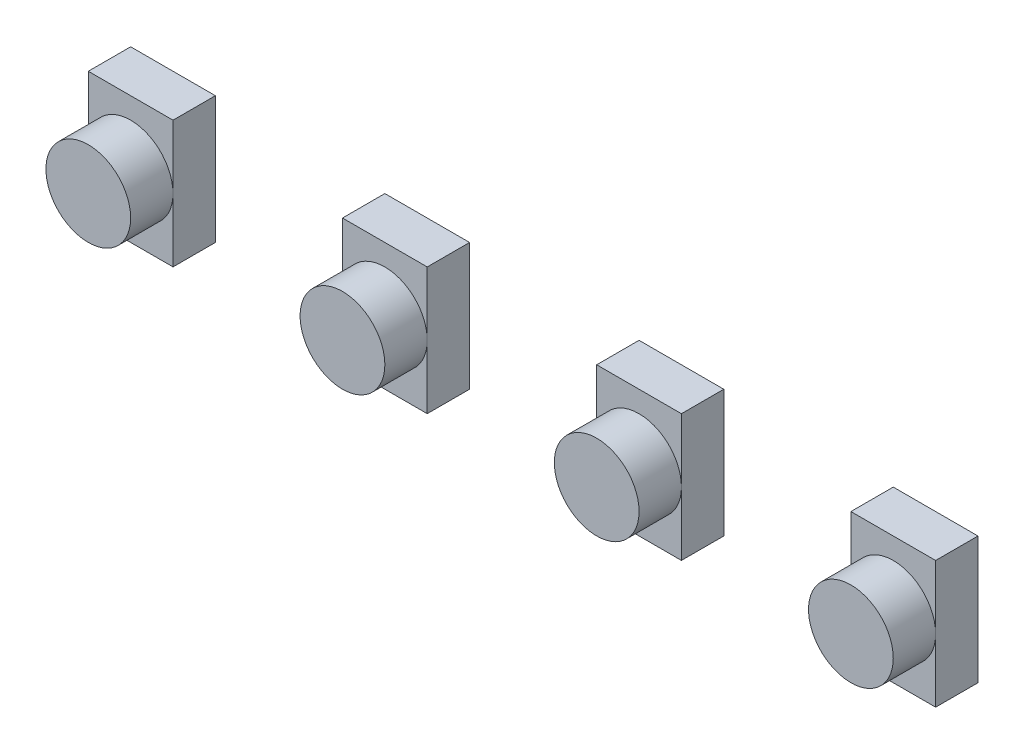
SolidWorks part; units mm, degrees
ref_plane "前视基准面" through (0, 0, 0) normal (0, 0, 1) x (1, 0, 0)
ref_plane "上视基准面" through (0, 0, 0) normal (0, 1, 0) x (1, 0, 0)
ref_plane "右视基准面" through (0, 0, 0) normal (1, 0, 0) x (0, 0, -1)
sketch "草图1" plane through (0, 0, 0) normal (0, 0, 1) x (1, 0, 0)
  line L0 (86.4677, 31.7854) -> (116.4677, 31.7854) construction
  line L1 (111.4677, 39.2854) -> (121.4677, 39.2854)
  line L2 (111.4677, 39.2854) -> (111.4677, 24.2854)
  line L3 (111.4677, 24.2854) -> (121.4677, 24.2854)
  line L4 (121.4677, 39.2854) -> (121.4677, 24.2854)
  line L5 (111.4677, 39.2854) -> (121.4677, 24.2854) construction
  line L6 (111.4677, 24.2854) -> (121.4677, 39.2854) construction
  line L7 (81.4677, 39.2854) -> (91.4677, 39.2854)
  line L8 (81.4677, 39.2854) -> (81.4677, 24.2854)
  line L9 (81.4677, 24.2854) -> (91.4677, 24.2854)
  line L10 (91.4677, 39.2854) -> (91.4677, 24.2854)
  line L11 (81.4677, 39.2854) -> (91.4677, 24.2854) construction
  line L12 (81.4677, 24.2854) -> (91.4677, 39.2854) construction
  line L14 (51.4677, 39.2854) -> (61.4677, 39.2854)
  line L15 (51.4677, 39.2854) -> (51.4677, 24.2854)
  line L16 (51.4677, 24.2854) -> (61.4677, 24.2854)
  line L17 (61.4677, 39.2854) -> (61.4677, 24.2854)
  line L18 (51.4677, 39.2854) -> (61.4677, 24.2854) construction
  line L19 (51.4677, 24.2854) -> (61.4677, 39.2854) construction
  line L20 (141.4677, 39.2854) -> (151.4677, 39.2854)
  line L21 (141.4677, 39.2854) -> (141.4677, 24.2854)
  line L22 (141.4677, 24.2854) -> (151.4677, 24.2854)
  line L23 (151.4677, 39.2854) -> (151.4677, 24.2854)
  line L24 (141.4677, 39.2854) -> (151.4677, 24.2854) construction
  line L25 (141.4677, 24.2854) -> (151.4677, 39.2854) construction
  point P0 (116.4677, 31.7854)
  point P5 (86.4677, 31.7854)
  point P12 (56.4677, 31.7854)
  point P17 (146.4677, 31.7854)
  dimension "D1" = 15
  dimension "D2" = 10
  dimension "D3" = 15
  dimension "D4" = 10
  dimension "D5" = 30
  dimension "D6" = 15
  dimension "D7" = 10
  dimension "D8" = 30
  dimension "D9" = 15
  dimension "D10" = 10
  dimension "D11" = 30
extrude "凸台-拉伸1" add sketch "草图1" along normal blind 5
sketch "草图3" plane through (0, 0, 5) normal (0, 0, 1) x (1, 0, 0)
  circle A0 centre (116.4677, 31.7854) radius 5
  circle A1 centre (86.4677, 31.7854) radius 5
  circle A2 centre (56.4677, 31.7854) radius 5
  circle A3 centre (146.4677, 31.7854) radius 5
extrude "凸台-拉伸2" add sketch "草图3" along normal blind 5
